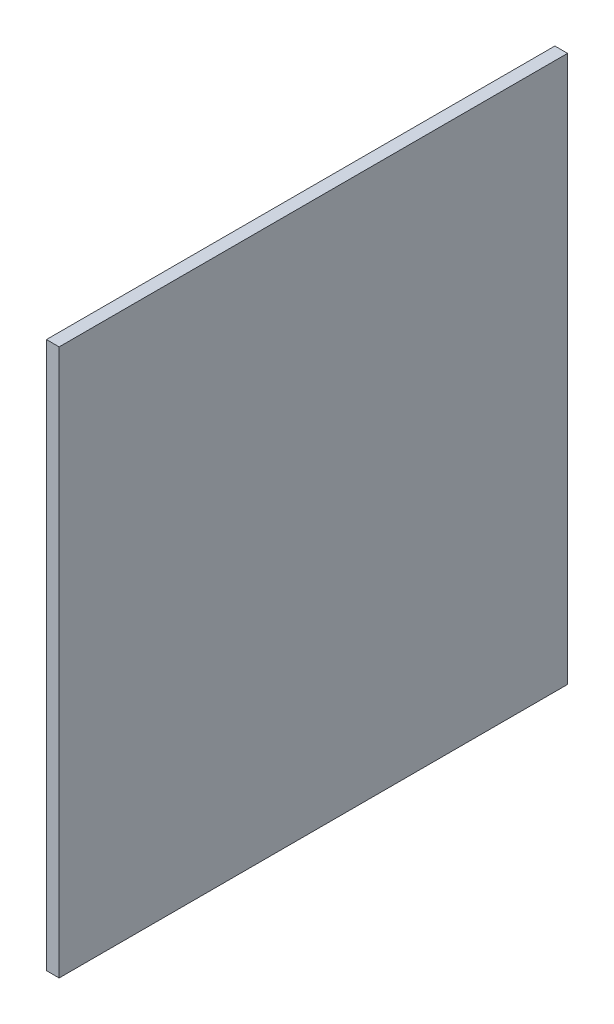
SolidWorks part; units mm, degrees
material "유리"
ref_plane "정면" through (0, 0, 0) normal (0, 0, 1) x (1, 0, 0)
ref_plane "윗면" through (0, 0, 0) normal (0, 1, 0) x (1, 0, 0)
ref_plane "우측면" through (0, 0, 0) normal (1, 0, 0) x (0, 0, -1)
sketch "스케치1" plane through (0, 0, 0) normal (1, 0, 0) x (0, 0, -1)
  line L1 (0, 0) -> (200, 0)
  line L2 (0, 0) -> (0, 215)
  line L3 (0, 215) -> (200, 215)
  line L4 (200, 0) -> (200, 215)
  dimension "D1" = 200
  dimension "D2" = 215
extrude "보스-돌출1" add sketch "스케치1" along normal blind 5
